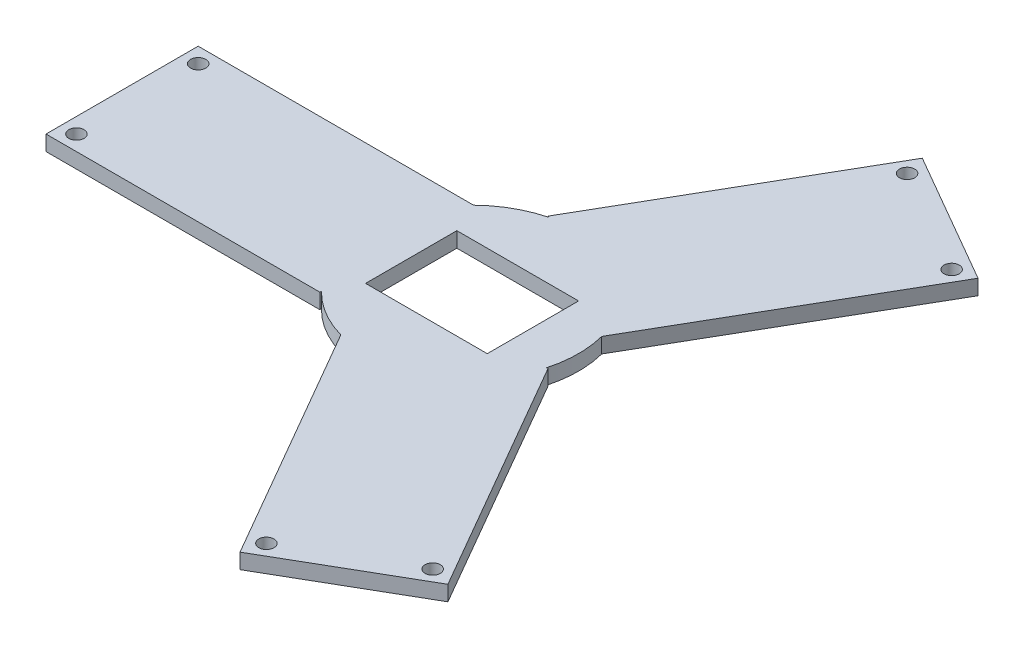
SolidWorks part; units mm, degrees
ref_plane "Plan de face" through (0, 0, 0) normal (0, 0, 1) x (1, 0, 0)
ref_plane "Plan de dessus" through (0, 0, 0) normal (0, 1, 0) x (1, 0, 0)
ref_plane "Plan de droite" through (0, 0, 0) normal (1, 0, 0) x (0, 0, -1)
sketch "Esquisse3" plane through (0, 0, 0) normal (0, 1, 0) x (1, 0, 0)
  line L0 (-150.1573, 0) -> (189.6273, 0) construction
  line L1 (-83.8395, -145.9242) -> (87.7229, 151.2306) construction
  line L2 (-78.0725, 135.2255) -> (117.7517, -203.9519) construction
  line L3 (-125, 131.2995) -> (-125, -153.5705) construction
  line L4 (-25, -25) -> (-115, -25)
  line L6 (-25, 25) -> (-24.4949, 25)
  line L7 (-115, -25) -> (-115, 25)
  line L8 (-25, -25) -> (-115, 25) construction
  line L9 (-25, 25) -> (-115, -25) construction
  line L10 (-24.4949, 25) -> (-115, 25)
  line L11 (33.8981, 8.7132) -> (79.1506, 87.0929)
  line L12 (35.8494, 112.0929) -> (79.1506, 87.0929)
  line L13 (-9.1506, 34.1506) -> (35.8494, 112.0929)
  line L14 (-9.4032, -33.7132) -> (35.8494, -112.0929)
  line L15 (79.1506, -87.0929) -> (35.8494, -112.0929)
  line L16 (34.1506, -9.1506) -> (79.1506, -87.0929)
  line L17 (-24.4949, 25) -> (-25, -25)
  line L18 (-9.1506, 34.1506) -> (33.8981, 8.7132)
  line L19 (-9.4032, -33.7132) -> (34.1506, -9.1506)
  circle A0 centre (0, 0) radius 125
  circle A1 centre (0, 0) radius 35
  circle A2 centre (0, 0) radius 125
  circle A3 centre (0, 0) radius 125
  circle A4 centre (-110, -20) radius 2.5
  circle A5 centre (-110, 20) radius 2.5
  circle A6 centre (37.6795, 105.2628) radius 2.5
  circle A7 centre (72.3205, 85.2628) radius 2.5
  circle A8 centre (72.3205, -85.2628) radius 2.5
  circle A9 centre (37.6795, -105.2628) radius 2.5
  point P9 (-70, 0)
  point P32 (0, 0)
  point P43 (0, 0)
  dimension "D1" = 250
  dimension "D4" = 70
  dimension "D9" = 5
  dimension "D2" = 120
  dimension "D3" = 120
  dimension "D5" = 10
  dimension "D6" = 50
  dimension "D7" = 90
  dimension "D10" = 5
  dimension "D11" = 5
  dimension "D8" = 3
  dimension "D12" = 3
extrude "Boss.-Extru.3" add sketch "Esquisse3" along normal blind 5 contours A1 L6 L10 L7 L4 L17 | A1 L14 L15 L16 L19 | L19 A1 L18 L17 | A1 L11 L12 L13 L18 | L18 A1
ref_plane "Plan1" through (0, 25, 0) normal (0, 1, 0) x (1, 0, 0)
sketch "Esquisse4" plane through (0, 5, 0) normal (0, 1, 0) x (1, 0, 0)
  line L1 (20, -15) -> (-20, -15)
  line L2 (20, -15) -> (20, 15)
  line L3 (20, 15) -> (-20, 15)
  line L4 (-20, -15) -> (-20, 15)
  line L5 (20, -15) -> (-20, 15) construction
  line L6 (20, 15) -> (-20, -15) construction
  point P0 (0, 0)
  dimension "D1" = 40
  dimension "D2" = 30
extrude "Enlèv. mat.-Extru.1" cut sketch "Esquisse4" against normal through all
